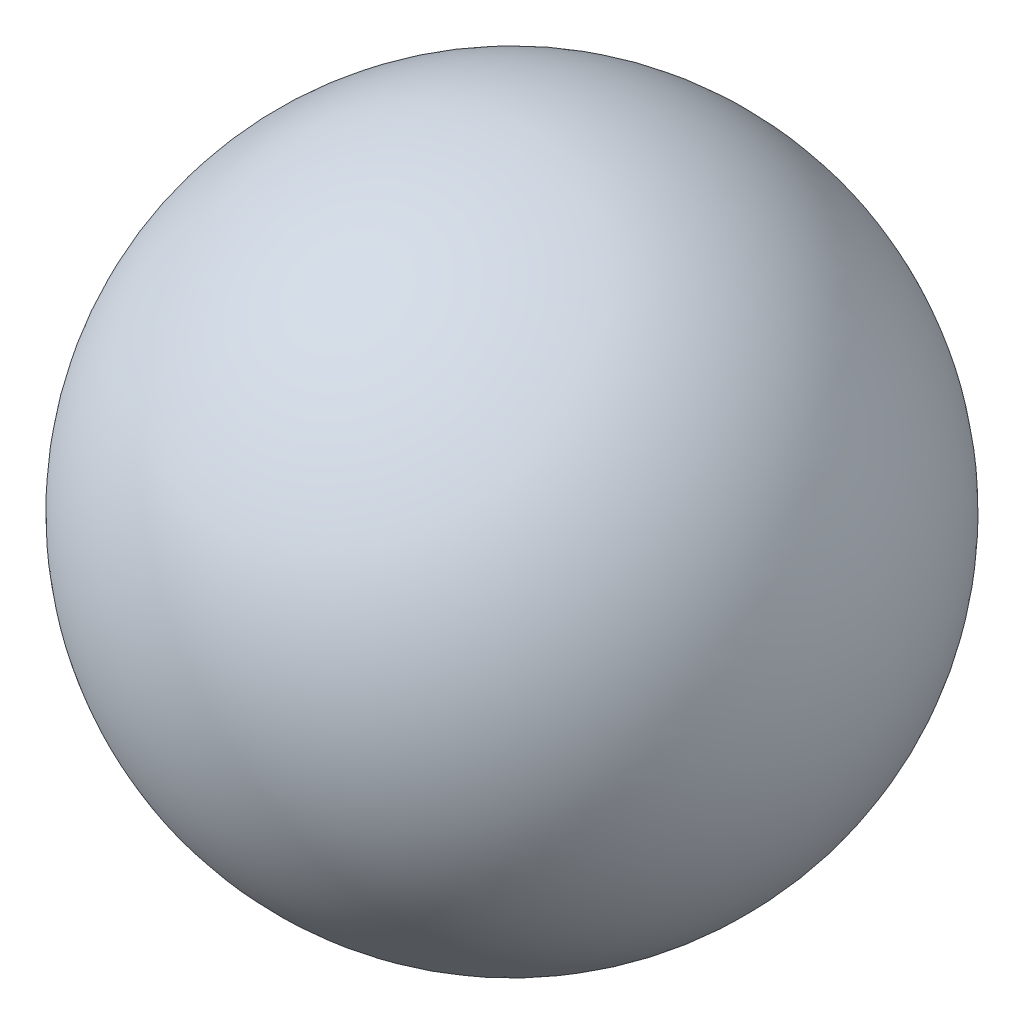
SolidWorks part; units mm, degrees
material "Stainless Steel (ferritic)"
ref_plane "Front Plane" through (0, 0, 0) normal (0, 0, 1) x (1, 0, 0)
ref_plane "Top Plane" through (0, 0, 0) normal (0, 1, 0) x (1, 0, 0)
ref_plane "Right Plane" through (0, 0, 0) normal (1, 0, 0) x (0, 0, -1)
sketch "Layout Sketch" plane through (0, 0, 0) normal (1, 0, 0) x (0, 0, -1)
  line L0 (-2.4892, 0) -> (2.4892, 0) construction
  line L1 (0, 6.35) -> (0, -6.35) construction
  line L2 (2.2403, 6.35) -> (-2.2403, 6.35)
  line L3 (-2.2403, 6.35) -> (-2.4892, 6.1011)
  line L4 (-2.4892, 6.1011) -> (-2.4892, 4.705)
  line L5 (-2.4892, 4.705) -> (-1.1063, 4.705)
  line L6 (2.4892, 4.705) -> (1.1063, 4.705)
  line L7 (2.4892, 6.1011) -> (2.4892, 4.705)
  line L8 (2.2403, 6.35) -> (2.4892, 6.1011)
  line L9 (0, 6.35) -> (0, 4.3656) construction
  line L10 (0, 4.3656) -> (0, 2.3813) construction
  arc A0 (-1.1063, 4.705) -> (1.1063, 4.705) centre (0, 4.3656) cw
  point P14 (0, 2.3813)
  dimension "Width" = 4.9784
  dimension "OD" = 12.7
  dimension "D1" = 45
  dimension "D2" = 0.2489
  dimension "Shaft Dia" = 4.7625
  dimension "D3" = 2.2126
  dimension "D4" = 0.3394
sketch "Bearing Ball Profile" plane through (0, 0, 0) normal (1, 0, 0) x (0, 0, -1)
  line L0 (-1.1572, 4.3656) -> (1.1572, 4.3656)
  arc A2 (-1.1572, 4.3656) -> (1.1572, 4.3656) centre (0, 4.3656) cw
  arc A3 (1.1063, 4.705) -> (-1.1063, 4.705) centre (0, 4.3656) ccw construction
revolve "Bearing Ball" add sketch "Bearing Ball Profile" angle 360 about L0
ref_point "Bearing Ball Center Point"
sketch "Ball Bearing Gear Profile" plane through (0, 0, 0) normal (0, 0, 1) x (1, 0, 0)
  circle A0 centre (0, 4.3656) radius 1.1572
  circle A1 centre (0, 4.3656) radius 1.1572
curve "Ball Bearing Gear Curve"
equation "\"D2@Layout Sketch\" = \"Width@Layout Sketch\" * .05"
equation "\"D3@Layout Sketch\" = \"Width@Layout Sketch\" / 2.25"
equation "\"D4@Layout Sketch\" =  (  (  ( \"OD@Layout Sketch\" - \"Width@Layout Sketch\" )  / 2 )  / 3.25 )  / 3.5"
